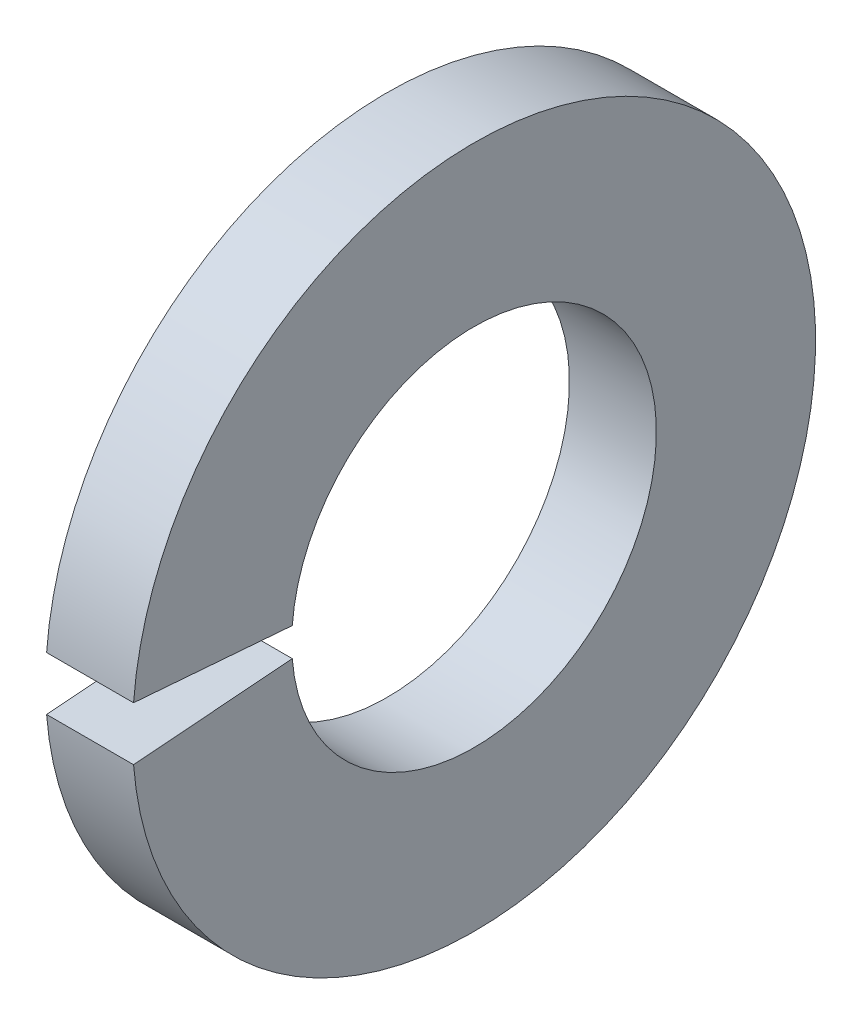
SolidWorks part; units mm, degrees
ref_plane "Plane1" through (0, 0, 0) normal (0, 0, 1) x (1, 0, 0)
ref_plane "Plane2" through (0, 0, 0) normal (0, 1, 0) x (1, 0, 0)
ref_plane "Plane3" through (0, 0, 0) normal (1, 0, 0) x (0, 0, -1)
sketch "Sketch1" plane through (0, 0, 0) normal (0, 0, 1) x (1, 0, 0)
  line L0 (-34.925, 0) -> (9.525, 0) construction
  line L1 (0, 3.302) -> (0, 6.1849)
  line L2 (0, 6.1849) -> (-1.5748, 6.1849)
  line L3 (-1.5748, 6.1849) -> (-1.5748, 3.302)
  line L4 (-1.5748, 3.302) -> (0, 3.302)
  dimension "Thickness" = 1.5748
  dimension "Inside_dia" = 6.604
  dimension "Outside_dia" = 12.3698
revolve "Base-Revolve" add sketch "Sketch1" angle 360 about L0
sketch "Sketch2" plane through (0, 0, 0) normal (-1, 0, 0) x (0, -1, 0)
  line L0 (0, 0) -> (0.495, 6.2892)
  line L1 (0, -3.175) -> (0, 12.7) construction
  line L2 (0, 0) -> (-0.495, 6.2892)
  arc A0 (0.495, 6.2892) -> (-0.495, 6.2892) centre (0, 0) ccw
  dimension "Gap_ang" = 9
  dimension "D1" = 6.3086
extrude "Gap" cut sketch "Sketch2" along normal through all
equation "\"D1@Sketch2\" = \"Outside_dia@Sketch1\" * 0.51"
